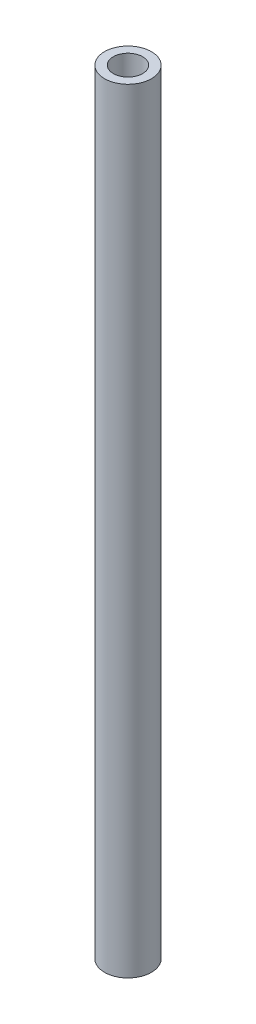
SolidWorks part; units mm, degrees
material "7075-O (SS)"
ref_plane "Front Plane" through (0, 0, 0) normal (0, 0, 1) x (1, 0, 0)
ref_plane "Top Plane" through (0, 0, 0) normal (0, 1, 0) x (1, 0, 0)
ref_plane "Right Plane" through (0, 0, 0) normal (1, 0, 0) x (0, 0, -1)
sketch "Sketch1" plane through (0, 0, 0) normal (0, 1, 0) x (1, 0, 0)
  line L0 (-143.9942, 0) -> (160.8058, 0) construction
  line L1 (0, 109.6403) -> (0, -97.9453) construction
  circle A0 centre (0, 0) radius 25.4
  circle A2 centre (0, 0) radius 15.875
  point P11 (0, 0)
  dimension "D1" = 50.8
  dimension "D2" = 31.75
extrude "Boss-Extrude1" add sketch "Sketch1" along normal blind 838.2
sketch "Sketch2" plane through (0, 0, 0) normal (0, 0, 1) x (1, 0, 0)
  circle A0 centre (0, 38.1) radius 4.7625
  dimension "D2" = 9.525
  dimension "D1" = 38.1
sketch "Sketch5" plane through (0, 0, 0) normal (0, -1, 0) x (1, 0, 0)
  text T0 "B"
extrude "Cut-Extrude3" cut sketch "Sketch5" against normal blind 5.08
sketch "Sketch6" [suppressed] plane through (0, 1117.6, 0) normal (0, 1, 0) x (1, 0, 0)
  line L1 (-53.975, 53.975) -> (53.975, 53.975)
  line L2 (-53.975, 53.975) -> (-53.975, -53.975)
  line L3 (-53.975, -53.975) -> (53.975, -53.975)
  line L4 (53.975, 53.975) -> (53.975, -53.975)
  line L5 (-53.975, 53.975) -> (53.975, -53.975) construction
  line L6 (-53.975, -53.975) -> (53.975, 53.975) construction
  point P0 (0, 0)
  dimension "D1" = 107.95
  dimension "D2" = 107.95
extrude "Boss-Extrude2" [suppressed] add sketch "Sketch6" along normal blind 6.35
sketch "Sketch7" [suppressed] plane through (0, 1123.95, 0) normal (0, 1, 0) x (1, 0, 0)
  line L0 (-53.975, 53.975) -> (-53.975, -53.975) construction
  line L1 (53.975, 53.975) -> (-53.975, 53.975) construction
  line L2 (-53.975, 0) -> (53.975, 0) construction
  line L3 (53.975, -53.975) -> (53.975, 53.975) construction
  line L4 (0, 53.975) -> (0, -53.975) construction
  line L5 (-53.975, -53.975) -> (53.975, -53.975) construction
  circle A0 centre (-28.575, 28.575) radius 4.7625
  circle A1 centre (-28.575, -28.575) radius 4.7625
  circle A2 centre (28.575, -28.575) radius 4.7625
  circle A3 centre (28.575, 28.575) radius 4.7625
  dimension "D1" = 25.4
  dimension "D2" = 25.4
  dimension "D3" = 9.525
extrude "Cut-Extrude4" [suppressed] cut sketch "Sketch7" against normal through all
sketch "Sketch8" [suppressed] plane through (0, 1123.95, 0) normal (0, 1, 0) x (1, 0, 0)
  text T0 "TOP"
extrude "Cut-Extrude6" [suppressed] cut sketch "Sketch8" against normal blind 2.54
sketch3d "3DSketch1"
  point P0 (2.0696, 469.989, -25.3155)
